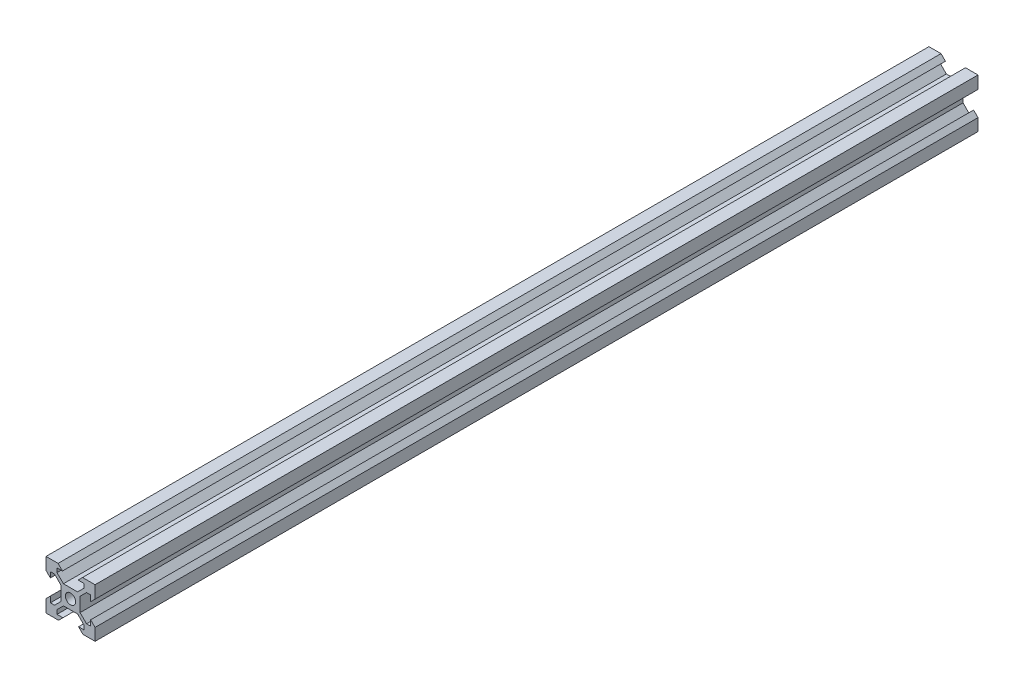
SolidWorks part; units mm, degrees
ref_plane "Front Plane" through (0, 0, 0) normal (0, 0, 1) x (1, 0, 0)
ref_plane "Top Plane" through (0, 0, 0) normal (0, 1, 0) x (1, 0, 0)
ref_plane "Right Plane" through (0, 0, 0) normal (1, 0, 0) x (0, 0, -1)
sketch "Sketch1"
  line L0 (3.6782, 7.2976) -> (17.6348, 7.2976) construction
  line L1 (0, 0) -> (59.361, 0) construction
  line L6 (-10, -10) -> (10, 10) construction
  line L7 (-10, 10) -> (10, -10) construction
  line L8 (-10, 10) -> (10, -10) construction
  line L9 (-10, -10) -> (10, 10) construction
  line L10 (-5.0746, 10) -> (-3.2822, 8.2076)
  line L11 (-3.2822, 8.2076) -> (-5.5259, 8.2076)
  line L12 (-5.5259, 8.2076) -> (-5.5259, 6.528)
  line L13 (-5.5259, 6.528) -> (-2.8971, 3.8992)
  line L14 (-2.8971, 3.8992) -> (2.8681, 3.8992)
  line L15 (2.8681, 3.8992) -> (5.4968, 6.528)
  line L16 (5.4968, 6.528) -> (5.4968, 8.2076)
  line L17 (5.4968, 8.2076) -> (3.0937, 8.2076)
  line L18 (3.0937, 8.2076) -> (4.8861, 10)
  line L19 (-10, 5.0746) -> (-10, 10)
  line L20 (-10, 10) -> (-5.0746, 10)
  line L21 (-6.528, -5.4968) -> (-8.2076, -5.4968)
  line L22 (-8.2076, -3.0937) -> (-10, -4.8861)
  line L23 (-8.2076, -5.4968) -> (-8.2076, -3.0937)
  line L24 (-6.528, 5.5259) -> (-3.8992, 2.8971)
  line L25 (-3.8992, -2.8681) -> (-6.528, -5.4968)
  line L26 (-3.8992, 2.8971) -> (-3.8992, -2.8681)
  line L28 (10, -10) -> (5.0746, -10)
  line L30 (-10, -4.8861) -> (-10, -10)
  line L31 (-8.2076, 5.5259) -> (-6.528, 5.5259)
  line L32 (-8.2076, 3.2822) -> (-8.2076, 5.5259)
  line L33 (-10, 5.0746) -> (-8.2076, 3.2822)
  line L34 (5.0746, -10) -> (3.2822, -8.2076)
  line L35 (3.2822, -8.2076) -> (5.5259, -8.2076)
  line L36 (5.5259, -8.2076) -> (5.5259, -6.528)
  line L37 (2.8971, -3.8992) -> (-2.8681, -3.8992)
  line L38 (-2.8681, -3.8992) -> (-5.4968, -6.528)
  line L39 (5.5259, -6.528) -> (2.8971, -3.8992)
  line L40 (-5.4968, -8.2076) -> (-3.0937, -8.2076)
  line L41 (-3.0937, -8.2076) -> (-4.8861, -10)
  line L42 (-5.4968, -6.528) -> (-5.4968, -8.2076)
  line L43 (-10, -10) -> (-4.8861, -10)
  line L44 (8.2076, 3.0937) -> (10, 4.8861)
  line L45 (8.2076, 5.4968) -> (8.2076, 3.0937)
  line L46 (6.528, 5.4968) -> (8.2076, 5.4968)
  line L47 (3.8992, 2.8681) -> (6.528, 5.4968)
  line L48 (3.8992, -2.8971) -> (3.8992, 2.8681)
  line L49 (6.528, -5.5259) -> (3.8992, -2.8971)
  line L50 (8.2076, -5.5259) -> (6.528, -5.5259)
  line L51 (8.2076, -3.2822) -> (8.2076, -5.5259)
  line L52 (10, -5.0746) -> (8.2076, -3.2822)
  line L53 (5.0746, -10) -> (10, -10)
  line L54 (10, 4.8861) -> (10, 10)
  line L56 (10, 10) -> (4.8861, 10)
  line L57 (5.0746, -10) -> (10, -10)
  line L60 (10, -10) -> (10, -5.0746)
  circle A0 centre (0, 0) radius 2.1
  point P2 (0, 0)
other "Pen Sketch1" parameters "D3"=2.0969, "D1"=797.2567, "D2"=2.8793
extrude "Boss-Extrude1" add sketch "Sketch1" along normal blind 360
